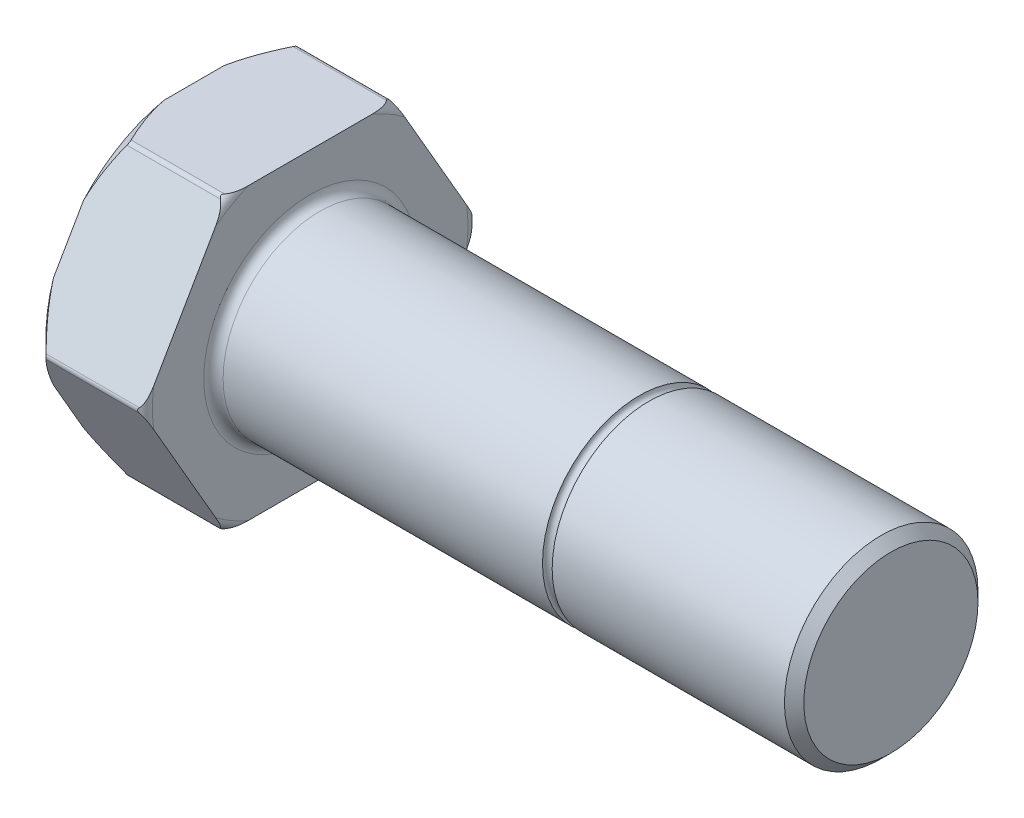
SolidWorks part; units mm, degrees
material "AISI 1010 Barra de acero laminada en caliente"
ref_plane "Alzado" through (0, 0, 0) normal (0, 0, 1) x (1, 0, 0)
ref_plane "Planta" through (0, 0, 0) normal (0, 1, 0) x (1, 0, 0)
ref_plane "Vista lateral" through (0, 0, 0) normal (1, 0, 0) x (0, 0, -1)
sketch "Croquis1" plane through (0, 0, 0) normal (0, 0, 1) x (1, 0, 0)
  line L0 (0, 0) -> (0, 17.3)
  line L1 (0, 17.3) -> (12, 17.3)
  line L2 (12, 17.3) -> (12, 10)
  line L3 (12, 10) -> (46, 10)
  line L4 (72, 10) -> (72, 0)
  line L5 (72, 0) -> (0, 0)
  line L6 (47, 10) -> (72, 10)
  arc A0 (46, 10) -> (47, 10) centre (46.5, 10) ccw
  dimension "D5" = 0.5
  dimension "D1" = 10
  dimension "D2" = 17.3
  dimension "D3" = 12
  dimension "D4" = 60
  dimension "D6" = 1
  dimension "D7" = 25
revolve "Revolución1" add sketch "Croquis1" angle 360 about L5
fillet "Redondeo1" radius 1 2 edges at (12, 0, -17.3) (12, 0, -10)
chamfer "Chaflán1" distance 1 angle 45 1 edges at (72, 0, -10)
sketch "Croquis4" plane through (0, 0, 0) normal (0, 0, 1) x (1, 0, 0)
  line L0 (0, 0) -> (71, 0) construction
  line L2 (0, 17.3) -> (0, 15.3)
  line L3 (0, 17.3) -> (0, -17.3) construction
  line L4 (0, 15.3) -> (2, 17.3)
  line L5 (11, 17.3) -> (0, 17.3) construction
  line L6 (2, 17.3) -> (0, 17.3)
  line L7 (71, -10) -> (71, 10) construction
  dimension "D1" = 2
  dimension "D2" = 2
revolve "Cortar-Revolución1" cut sketch "Croquis4" angle 360 about L0
sketch "Croquis2" plane through (0, 0, 0) normal (-1, 0, 0) x (0, 0, 1)
  line L1 (8.65, 14.9822) -> (-8.65, 14.9822)
  line L2 (-8.65, 14.9822) -> (-17.3, 0)
  line L3 (-17.3, 0) -> (-8.65, -14.9822)
  line L4 (-8.65, -14.9822) -> (8.65, -14.9822)
  line L5 (8.65, -14.9822) -> (17.3, 0)
  line L6 (17.3, 0) -> (8.65, 14.9822)
  circle A0 centre (0, 0) radius 14.9822 construction
  circle A1 centre (0, 0) radius 18.1223
  dimension "D2" = 36.2446
  dimension "D1" = 29.9645
extrude "Cortar-Extruir1" cut sketch "Croquis2" against normal up to next
fillet "Redondeo3" radius 0.5 6 edges at (6.5, 14.9822, 8.65) (6.5, 0, 17.3) (6.5, -14.9822, 8.65) (6.5, 14.9822, -8.65) (6.5, 0, -17.3) (6.5, -14.9822, -8.65)
